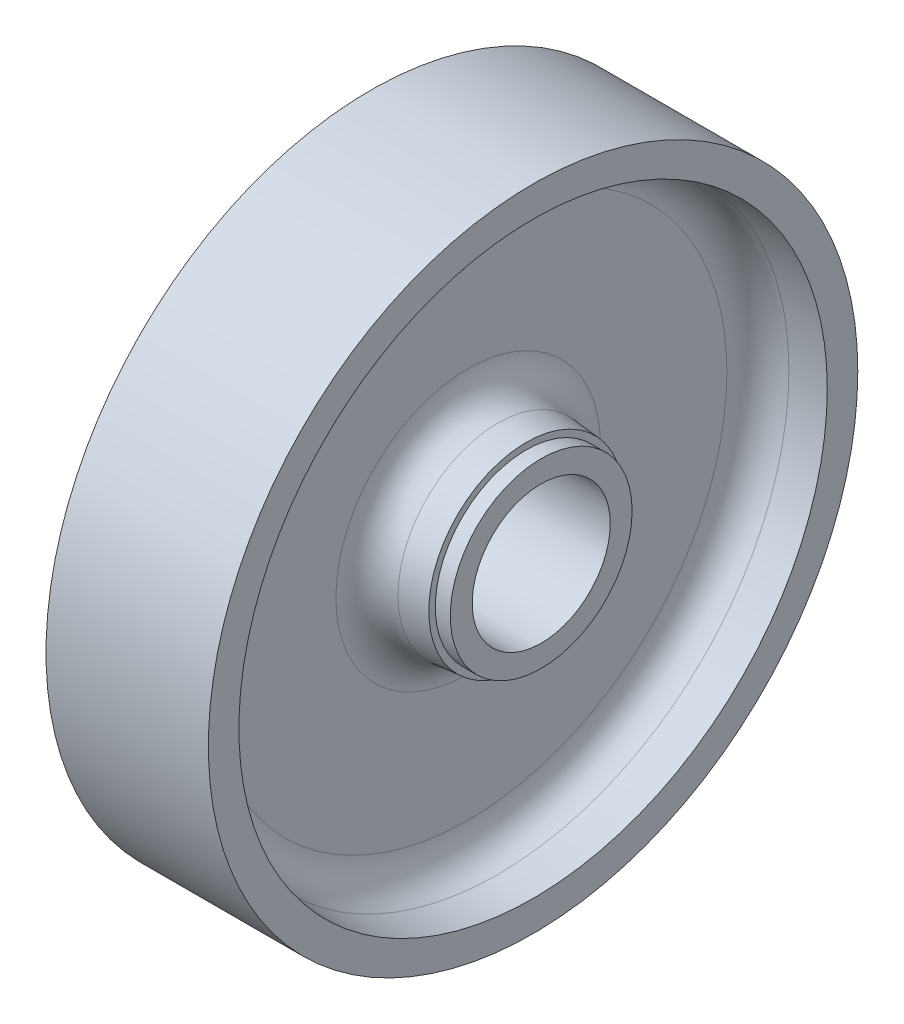
SolidWorks part; units mm, degrees
ref_plane "Plano frontal" through (0, 0, 0) normal (0, 0, 1) x (1, 0, 0)
ref_plane "Plano superior" through (0, 0, 0) normal (0, 1, 0) x (1, 0, 0)
ref_plane "Plano direito" through (0, 0, 0) normal (1, 0, 0) x (0, 0, -1)
sketch "Esboço1" plane through (0, 0, 0) normal (0, 0, 1) x (1, 0, 0)
  line L0 (-14.5288, 17.78) -> (-17.4625, 17.78)
  line L1 (-17.4625, 17.78) -> (-17.4625, 13.5001)
  line L2 (-17.4625, 13.5001) -> (17.4625, 13.5001)
  line L3 (17.4625, 13.5001) -> (17.4625, 17.78)
  line L4 (17.4625, 17.78) -> (14.5288, 17.78)
  line L5 (14.5288, 17.78) -> (14.5288, 19.05)
  line L6 (14.5288, 19.05) -> (8.9716, 19.5362)
  line L7 (3.175, 25.862) -> (3.175, 50.6012)
  line L8 (8.9716, 56.927) -> (15.875, 57.531)
  line L9 (15.875, 57.531) -> (15.875, 63.5)
  line L10 (15.875, 63.5) -> (-15.875, 63.5)
  line L11 (-15.875, 63.5) -> (-15.875, 57.531)
  line L12 (-15.875, 57.531) -> (-8.9716, 56.927)
  line L13 (-3.175, 50.6012) -> (-3.175, 25.862)
  line L14 (-8.9716, 19.5362) -> (-14.5288, 19.05)
  line L15 (-14.5288, 19.05) -> (-14.5288, 17.78)
  line L16 (-17.4625, 0) -> (17.4625, 0) construction
  arc A0 (8.9716, 19.5362) -> (3.175, 25.862) centre (9.525, 25.862) cw
  arc A1 (3.175, 50.6012) -> (8.9716, 56.927) centre (9.525, 50.6012) cw
  arc A2 (-8.9716, 56.927) -> (-3.175, 50.6012) centre (-9.525, 50.6012) cw
  arc A3 (-3.175, 25.862) -> (-8.9716, 19.5362) centre (-9.525, 25.862) cw
revolve "Revolução1" add sketch "Esboço1" angle 360 about L16
